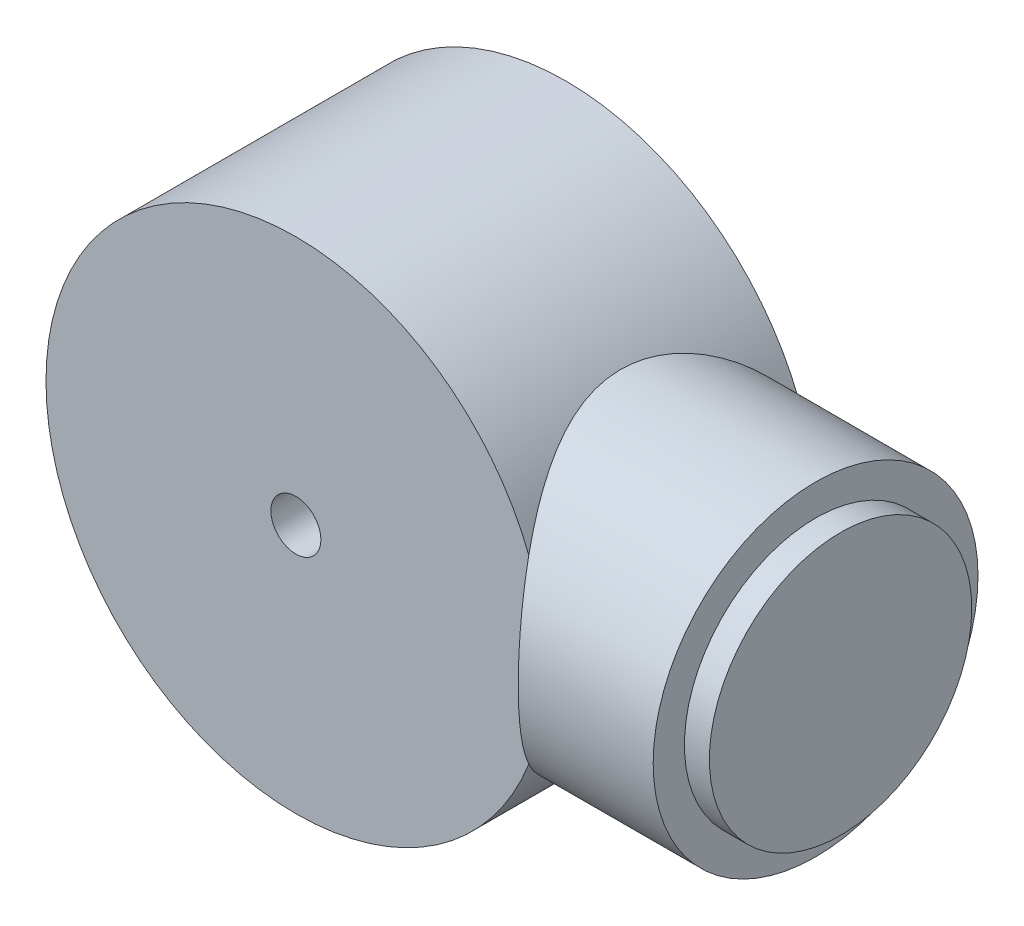
SolidWorks part; units mm, degrees
ref_plane "Front Plane" through (0, 0, 0) normal (0, 0, 1) x (1, 0, 0)
ref_plane "Top Plane" through (0, 0, 0) normal (0, 1, 0) x (1, 0, 0)
ref_plane "Right Plane" through (0, 0, 0) normal (1, 0, 0) x (0, 0, -1)
sketch "Sketch1" plane through (0, 0, 0) normal (0, 0, 1) x (1, 0, 0)
  circle A0 centre (0, 0) radius 50
  dimension "D1" = 100
extrude "Boss-Extrude1" add sketch "Sketch1" along normal blind 54 contours A0
ref_plane "Plane1" through (77, 0, 0) normal (1, 0, 0) x (0, 0, -1)
sketch "Sketch3" plane through (77, 0, 0) normal (1, 0, 0) x (0, 0, -1)
  line L0 (-54, 50) -> (-54, -50) construction
  circle A0 centre (-27, 0) radius 32.5
  dimension "D1" = 65
  dimension "D2" = 27
extrude "Boss-Extrude2" add sketch "Sketch3" against normal up to surface (27 mm away) contours A0 up to face at (50, 0, 54)
sketch "Sketch4" plane through (77, 0, 0) normal (1, 0, 0) x (0, 0, -1)
  circle A0 centre (-27, 0) radius 26.25
  dimension "D1" = 52.5
extrude "Boss-Extrude3" add sketch "Sketch4" along normal blind 5 contours A0
sketch "Sketch5" plane through (0, 0, 54) normal (0, 0, 1) x (1, 0, 0)
  circle A0 centre (0, 0) radius 5
extrude "Cut-Extrude1" cut sketch "Sketch5" against normal blind 500
